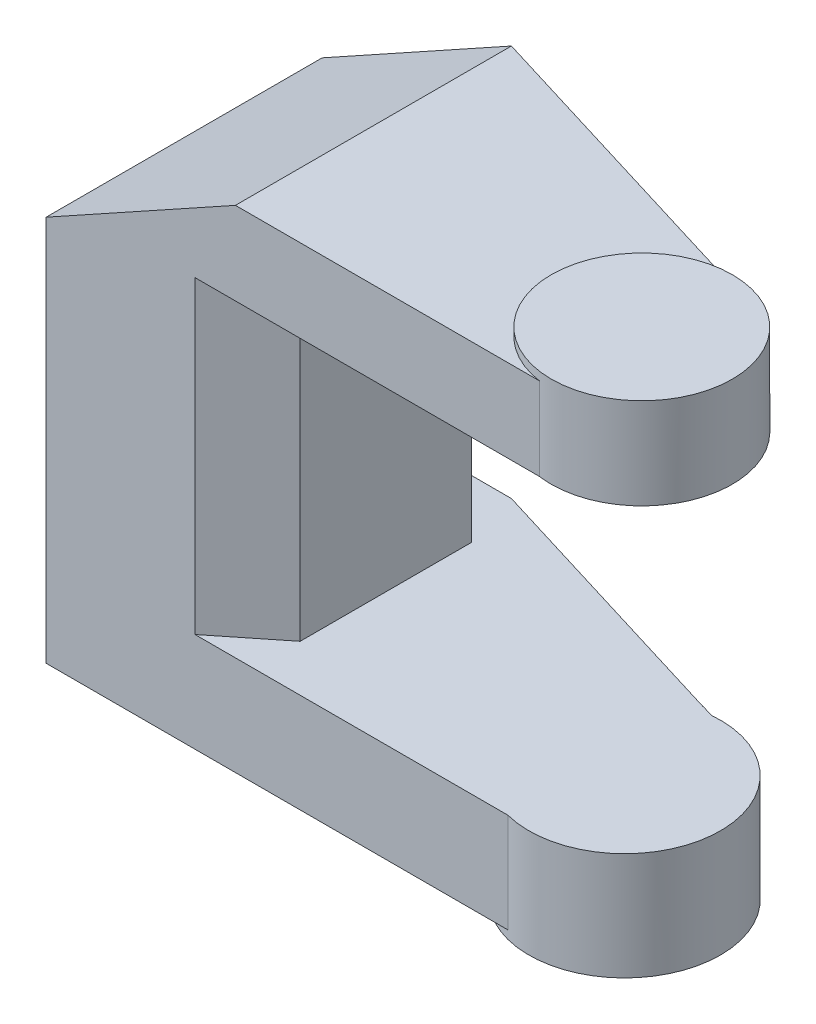
SolidWorks part; units mm, degrees
ref_plane "Front Plane" through (0, 0, 0) normal (0, 0, 1) x (1, 0, 0)
ref_plane "Top Plane" through (0, 0, 0) normal (0, 1, 0) x (1, 0, 0)
ref_plane "Right Plane" through (0, 0, 0) normal (1, 0, 0) x (0, 0, -1)
sketch "Sketch2" plane through (0, 0, 0) normal (0, 0, 1) x (1, 0, 0)
  line L0 (0, 0) -> (0, 350)
  line L1 (0, 350) -> (171.438, 445)
  line L2 (171.438, 445) -> (421.438, 445)
  line L3 (421.438, 445) -> (421.438, 370)
  line L4 (421.438, 370) -> (134.8087, 370)
  line L5 (134.8087, 370) -> (134.8087, 90)
  line L6 (134.8087, 90) -> (360, 90)
  line L7 (360, 90) -> (360, 0)
  line L8 (360, 0) -> (0, 0)
  dimension "D1" = 350
  dimension "D2" = 196
  dimension "D3" = 360
  dimension "D4" = 280
  dimension "D5" = 250
  dimension "D6" = 75
  dimension "D7" = 90
extrude "Boss-Extrude1" add sketch "Sketch2" against normal blind 250 contours L8 L0 L1 L2 L3 L4 L5 L6 L7
sketch "Sketch3" plane through (0, 0, 0) normal (0, 0, 1) x (1, 0, 0)
  line L0 (360, 90) -> (440, 90)
  line L1 (134.8087, 90) -> (360, 90) construction
  line L2 (360, 90) -> (360, 0) construction
  line L3 (440, 90) -> (440, 0)
  line L4 (440, 0) -> (360, 0)
  line L5 (360, 90) -> (360, 0)
  dimension "D1" = 80
extrude "Boss-Extrude3" add sketch "Sketch3" against normal blind 250
sketch "Sketch4" plane through (0, 445, 0) normal (0, 1, 0) x (1, 0, 0)
  line L0 (171.438, 250) -> (421.438, 173.5673)
  line L1 (421.438, 250) -> (421.438, 0) construction
  line L2 (421.438, 173.5673) -> (421.438, 250)
  line L3 (421.438, 250) -> (171.438, 250)
  line L4 (171.438, 250) -> (171.438, 0) construction
  line L5 (171.438, 250) -> (458.3295, 162.2885)
  dimension "D1" = 73
extrude "Cut-Extrude1" cut sketch "Sketch4" against normal blind 500 contours L3 L0 L2
sketch "Sketch5" plane through (0, 90, 0) normal (0, 1, 0) x (1, 0, 0)
  line L0 (171.438, 250) -> (529.2926, 140.8372)
  line L1 (529.2926, 140.8372) -> (529.2926, 329.4906)
  line L2 (529.2926, 329.4906) -> (171.438, 250)
extrude "Cut-Extrude2" cut sketch "Sketch5" against normal blind 500
sketch "Sketch6" plane through (0, 445, 0) normal (0, 1, 0) x (1, 0, 0)
  line L0 (458.3668, 162.4109) -> (421.438, 173.5673)
  line L1 (458.3668, 162.4109) -> (458.3668, 0)
  line L2 (458.3668, 0) -> (419.2826, 0)
  line L3 (419.2826, 0) -> (421.438, 173.5673)
extrude "Boss-Extrude4" add sketch "Sketch6" against normal up to surface (75 mm away) up to face at (256.7863, 370, -134.7135)
sketch "Sketch7" plane through (0, 445, 0) normal (0, 1, 0) x (1, 0, 0)
  line L0 (458.3668, 0) -> (458.3668, 162.4109) construction
  circle A0 centre (458.3668, 81.2054) radius 82
  dimension "D1" = 164
extrude "Boss-Extrude5" add sketch "Sketch7" against normal up to surface (75 mm away) up to face at (296.5379, 370, -139.3297)
sketch "Sketch8" plane through (0, 90, 0) normal (0, 1, 0) x (1, 0, 0)
  line L0 (440, 168.0757) -> (440, 0) construction
  circle A0 centre (440, 84.0379) radius 86.8204
extrude "Boss-Extrude6" add sketch "Sketch8" against normal up to surface (90 mm away) up to face at (270.6163, 0, -145.0544)
sketch "Sketch9" plane through (0, 445, 0) normal (0, 1, 0) x (1, 0, 0)
  circle A0 centre (458.3668, 81.2054) radius 82
extrude "Boss-Extrude7" add sketch "Sketch9" along normal blind 7.5
sketch "Sketch10" plane through (0, 0, 0) normal (0, -1, 0) x (1, 0, 0)
  circle A0 centre (440, -84.0379) radius 86.8204
extrude "Boss-Extrude8" add sketch "Sketch10" along normal blind 7.5
sketch "Sketch11" plane through (0, 90, 0) normal (0, 1, 0) x (1, 0, 0)
  line L0 (134.8087, 0) -> (187.7802, 42.2953)
  line L1 (187.7802, 42.2953) -> (187.7802, 197.6001)
  line L2 (187.7802, 197.6001) -> (134.8087, 250)
  line L3 (134.8087, 250) -> (134.8087, 0)
extrude "Boss-Extrude9" add sketch "Sketch11" along normal up to surface (280 mm away) up to face at (309.0267, 370, -138.6497)
